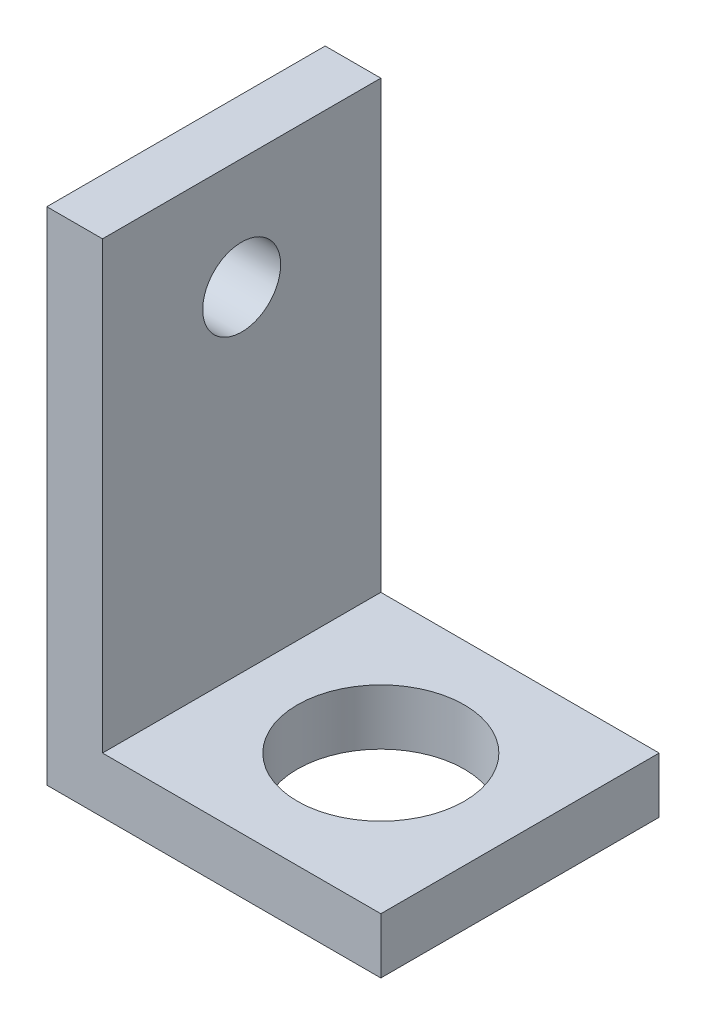
SolidWorks part; units mm, degrees
ref_plane "Front Plane" through (0, 0, 0) normal (0, 0, 1) x (1, 0, 0)
ref_plane "Top Plane" through (0, 0, 0) normal (0, 1, 0) x (1, 0, 0)
ref_plane "Right Plane" through (0, 0, 0) normal (1, 0, 0) x (0, 0, -1)
sketch "Sketch1" plane through (0, 0, 0) normal (0, 0, 1) x (1, 0, 0)
  line L0 (0, 80) -> (0, 0)
  line L1 (0, 0) -> (50, 0)
  point P3 (51.8421, 0)
  dimension "D1" = 80
  dimension "D2" = 50
extrude "Extrude-Thin1" add sketch "Sketch1" along normal blind 50 thin contours L0 L1
sketch "Sketch2" plane through (0, 0, 0) normal (0, 1, 0) x (1, 0, 0)
  line L0 (50, -50) -> (50, 0) construction
  line L1 (0, 0) -> (50, 0) construction
  circle A0 centre (25, -25) radius 15
  point P4 (50, -25)
  point P7 (25, 0)
  dimension "D1" = 30
extrude "Cut-Extrude1" cut sketch "Sketch2" against normal through all
sketch "Sketch3" plane through (0, 0, 0) normal (1, 0, 0) x (0, 0, -1)
  line L0 (-50, 80) -> (0, 80) construction
  circle A0 centre (-25, 60) radius 7
  point P4 (-25, 80)
  dimension "D1" = 14
  dimension "D2" = 20
extrude "Cut-Extrude2" cut sketch "Sketch3" against normal through all
